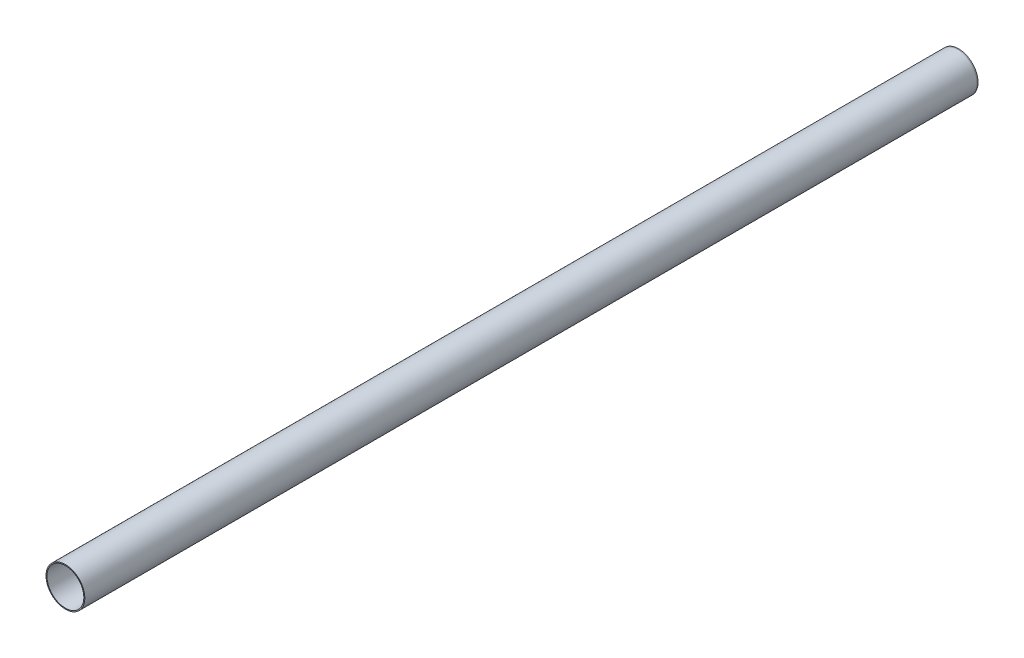
SolidWorks part; units mm, degrees
ref_plane "Front Plane" through (0, 0, 0) normal (0, 0, 1) x (1, 0, 0)
ref_plane "Top Plane" through (0, 0, 0) normal (0, 1, 0) x (1, 0, 0)
ref_plane "Right Plane" through (0, 0, 0) normal (1, 0, 0) x (0, 0, -1)
sketch "Sketch1" plane through (0, 0, 0) normal (0, 1, 0) x (1, 0, 0)
  line L0 (0, 0) -> (0, 460)
  dimension "D1" = 460
other "Pipe 26.9 X 3.2(1)"
ref_plane "Plane1" through (0, 0, 0) normal (0, 0, -1) x (-1, 0, 0)
sketch "Sketch11" plane through (0, 0, 0) normal (0, 0, -1) x (-1, 0, 0)
  circle A0 centre (0, 0) radius 9.5
  circle A1 centre (0, 0) radius 10
  point P3 (0, 10)
  point P5 (-10, 0)
  point P6 (0, -10)
  point P7 (10, 0)
  point P8 (0, 0)
  dimension "19" = 19
  dimension "Out_dia" = 20
sketch "Sketch13" plane through (0, 0, -460) normal (0, 0, -1) x (-1, 0, 0)
  circle A1 centre (0, 0) radius 10
  circle A2 centre (0, 0) radius 10
  dimension "D1" = 0
extrude "Boss-Extrude2" add sketch "Sketch13" along normal blind 0.5 separate body
